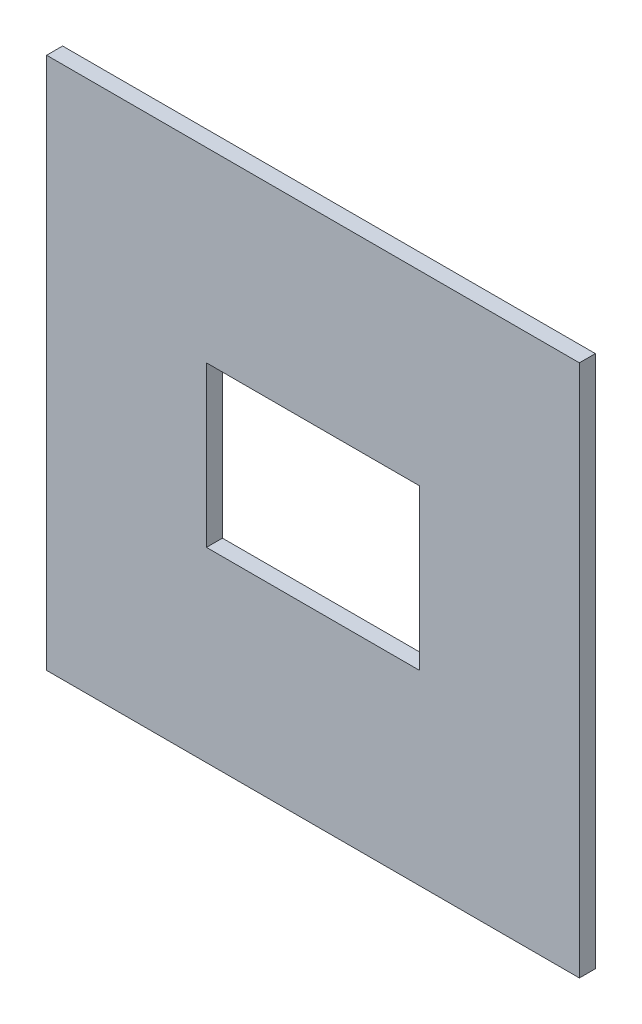
SolidWorks part; units mm, degrees
material "3.0205 (EN-AW 1200)"
ref_plane "Piano frontale" through (0, 0, 0) normal (0, 0, 1) x (1, 0, 0)
ref_plane "Piano superiore" through (0, 0, 0) normal (0, 1, 0) x (1, 0, 0)
ref_plane "Piano destro" through (0, 0, 0) normal (1, 0, 0) x (0, 0, -1)
sketch "Schizzo1" plane through (0, 0, 0) normal (0, 0, 1) x (1, 0, 0)
  line L1 (-250, 250) -> (250, 250)
  line L2 (-250, 250) -> (-250, -250)
  line L3 (-250, -250) -> (250, -250)
  line L4 (250, 250) -> (250, -250)
  line L5 (-250, 250) -> (250, -250) construction
  line L6 (-250, -250) -> (250, 250) construction
  point P0 (0, 0)
  dimension "D1" = 500
  dimension "D2" = 500
extrude "Estrusione-Estrusione1" add sketch "Schizzo1" along normal blind 15
sketch "Schizzo2" plane through (0, 0, 15) normal (0, 0, 1) x (1, 0, 0)
  line L1 (-100, 75) -> (100, 75)
  line L2 (-100, 75) -> (-100, -75)
  line L3 (-100, -75) -> (100, -75)
  line L4 (100, 75) -> (100, -75)
  line L5 (-100, 75) -> (100, -75) construction
  line L6 (-100, -75) -> (100, 75) construction
  point P0 (0, 0)
  dimension "D1" = 200
  dimension "D2" = 150
extrude "Taglio-Estrusione1" cut sketch "Schizzo2" against normal blind 15
